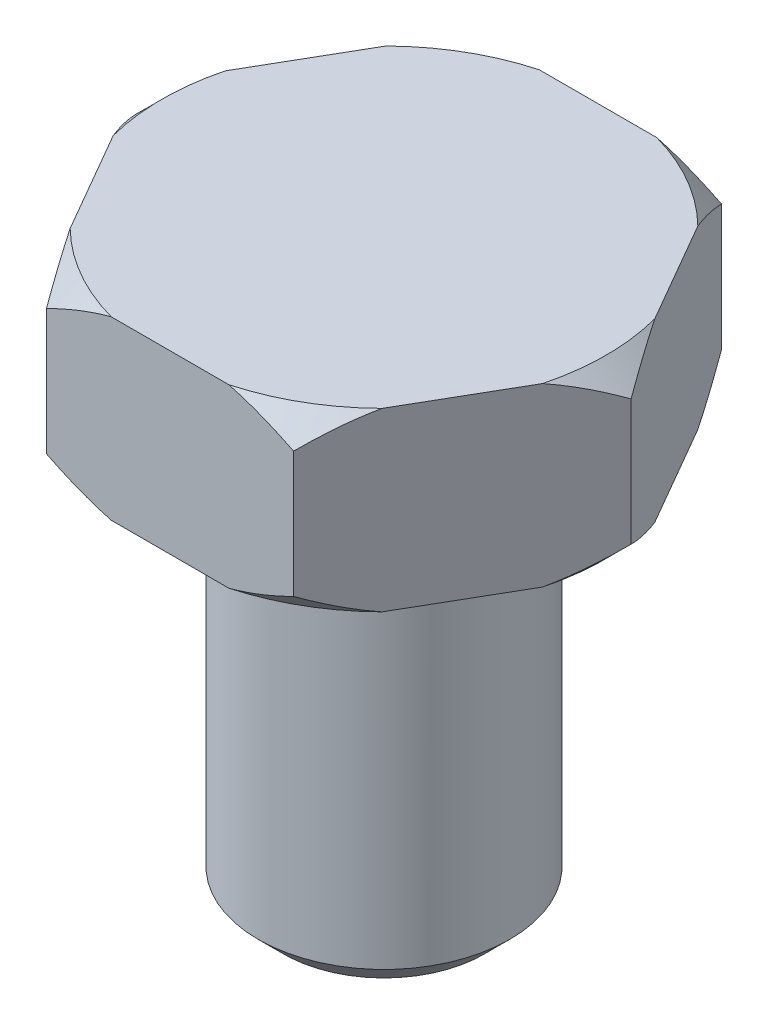
SolidWorks part; units mm, degrees
ref_plane "Спереди" through (0, 0, 0) normal (0, 0, 1) x (1, 0, 0)
ref_plane "Сверху" through (0, 0, 0) normal (0, 1, 0) x (1, 0, 0)
ref_plane "Справа" through (0, 0, 0) normal (1, 0, 0) x (0, 0, -1)
sketch "Эскиз1" plane through (0, 0, 0) normal (0, 1, 0) x (1, 0, 0)
  line L0 (-4.9075, 8.5) -> (4.9075, 8.5)
  line L1 (4.9075, 8.5) -> (9.815, 0)
  line L2 (9.815, 0) -> (4.9075, -8.5)
  line L3 (4.9075, -8.5) -> (-4.9075, -8.5)
  line L4 (-4.9075, -8.5) -> (-9.815, 0)
  line L5 (-9.815, 0) -> (-4.9075, 8.5)
  line L6 (-9.815, 0) -> (9.815, 0) construction
  circle A0 centre (0, 0) radius 9.815
  dimension "D1" = 120
  dimension "D5" = 17
  dimension "D2" = 120
extrude "Вытянуть1" add sketch "Эскиз1" against normal blind 7 contours L5 L6 L1 L0 | L6 L4 L3 L2
sketch "Эскиз5" plane through (0, -7, 0) normal (0, -1, 0) x (1, 0, 0)
  circle A0 centre (0, 0) radius 5
  dimension "D1" = 10
extrude "Вытянуть2" add sketch "Эскиз5" along normal blind 16
ref_axis "Ось1" through (0, -7, 0) along (0, -1, 0)
sketch "Эскиз4" plane through (0, 0, 0) normal (0, 0, 1) x (1, 0, 0)
  line L0 (-9.815, -1) -> (-8.815, 0)
  line L3 (-8.815, 0) -> (-9.815, 0)
  line L4 (-9.815, 0) -> (-9.815, -1)
  line L5 (-9.815, -6) -> (-8.815, -7)
  line L7 (-8.815, -7) -> (-9.815, -7)
  line L8 (-9.815, -7) -> (-9.815, -6)
  dimension "D1" = 1
  dimension "D2" = 1
  dimension "D3" = 1
  dimension "D4" = 1
revolve "Вырез-Повернуть1" cut sketch "Эскиз4" angle 360 about axis through (0, -7, 0) along (0, -1, 0)
chamfer "Фаска1" distance 1 angle 45 1 edges at (0, -23, -5)
